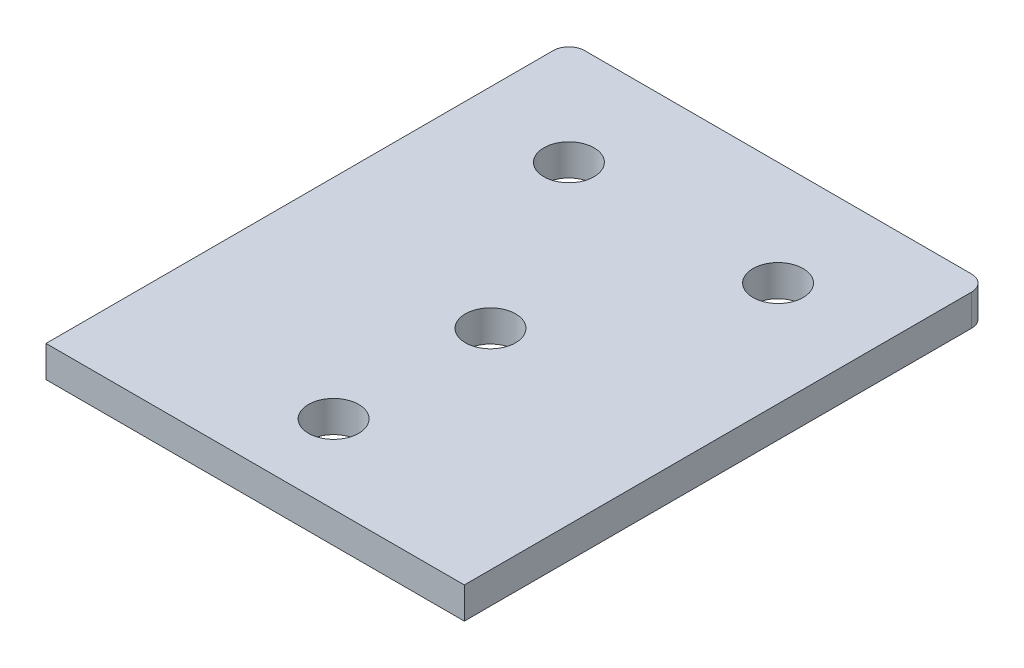
SolidWorks part; units mm, degrees
material "ABS"
ref_plane "Front Plane" through (0, 0, 0) normal (0, 0, 1) x (1, 0, 0)
ref_plane "Top Plane" through (0, 0, 0) normal (0, 1, 0) x (1, 0, 0)
ref_plane "Right Plane" through (0, 0, 0) normal (1, 0, 0) x (0, 0, -1)
sketch "Sketch1" plane through (0, 0, 0) normal (0, 1, 0) x (1, 0, 0)
  line L89 (-18.5, 10) -> (18.5, 10)
  line L90 (-20, 8.5) -> (-20, -40)
  line L91 (-20, -40) -> (20, -40)
  line L92 (20, 8.5) -> (20, -40)
  circle A0 centre (-10, 0) radius 2.4
  circle A1 centre (10, 0) radius 2.4
  arc A88 (-18.5, 10) -> (-20, 8.5) centre (-18.5, 8.5) ccw
  arc A89 (18.5, 10) -> (20, 8.5) centre (18.5, 8.5) cw
  circle A90 centre (0, -32.5) radius 2.4
  circle A91 centre (0, -17.5) radius 2.4
  point P1 (0, 0)
  point P8 (20, 10)
  dimension "D4" = 10
  dimension "D7" = 1.5
  dimension "D8" = 1.5
  dimension "D9" = 4.8
  dimension "D1" = 20
  dimension "D2" = 10
  dimension "D3" = 10
  dimension "D5" = 40
  dimension "D6" = 50
  dimension "D10" = 7.5
  dimension "D11" = 15
extrude "Boss-Extrude1" add sketch "Sketch1" along normal blind 3
